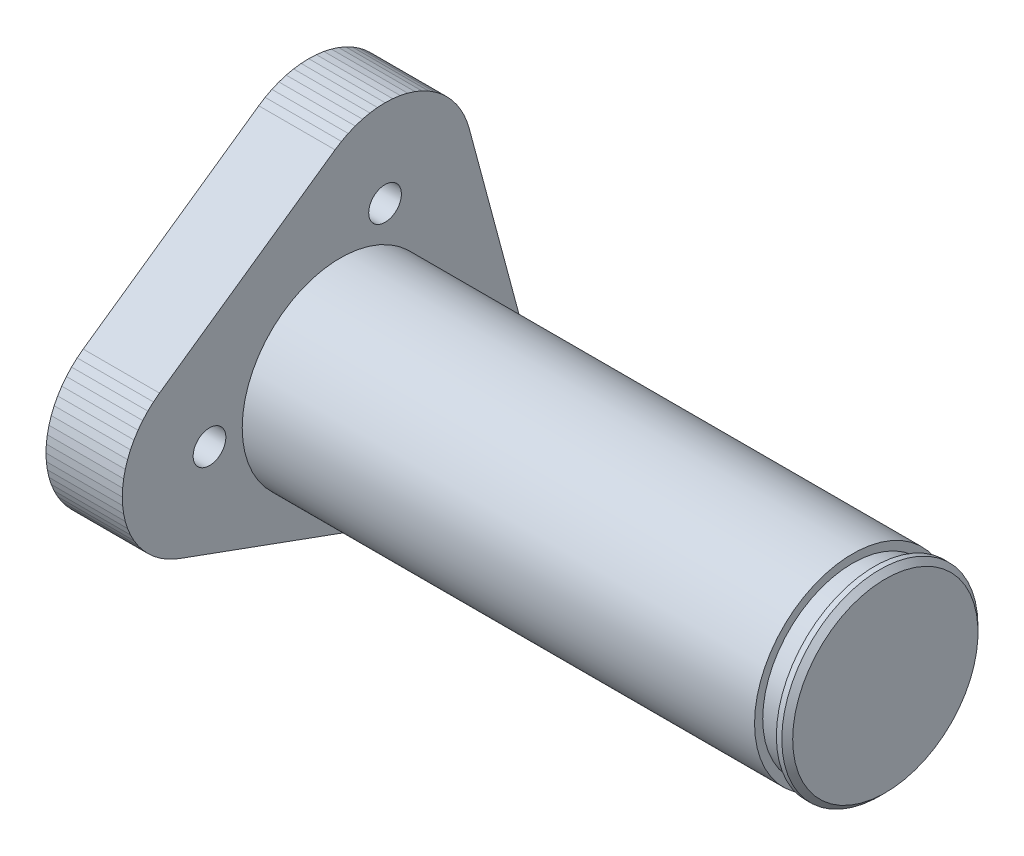
SolidWorks part; units mm, degrees
material "普通碳钢"
ref_plane "前视基准面" through (0, 0, 0) normal (0, 0, 1) x (1, 0, 0)
ref_plane "上视基准面" through (0, 0, 0) normal (0, 1, 0) x (1, 0, 0)
ref_plane "右视基准面" through (0, 0, 0) normal (1, 0, 0) x (0, 0, -1)
other "Configuration Table"
sketch "草图1" plane through (0, 0, 0) normal (0, 0, 1) x (1, 0, 0)
  line L0 (7, 0) -> (7, 9)
  line L1 (7, 9) -> (54, 9)
  line L2 (54, 9) -> (54, 8.25)
  line L3 (54, 8.25) -> (56, 8.25)
  line L4 (56, 8.25) -> (56, 9)
  line L5 (56, 9) -> (56.5, 9)
  line L6 (56.5, 9) -> (57, 8.5)
  line L7 (57, 8.5) -> (57, 0)
  line L8 (57, 0) -> (7, 0)
  line L9 (2, 0) -> (62, 0) construction
revolve "旋转1" add sketch "草图1" angle 360 about L9
sketch "草图2" plane through (0, 0, 0) normal (1, 0, 0) x (0, 0, -1)
  line L0 (-20, 0) -> (-19.9696, -0.6973)
  line L1 (-19.9696, -0.6973) -> (-19.8785, -1.3892)
  line L2 (-19.8785, -1.3892) -> (-19.7274, -2.0705)
  line L3 (-19.7274, -2.0705) -> (-19.5175, -2.7362)
  line L4 (-19.5175, -2.7362) -> (-19.2505, -3.3809)
  line L5 (-19.2505, -3.3809) -> (-18.9282, -4)
  line L6 (-18.9282, -4) -> (-18.5532, -4.5886)
  line L7 (-18.5532, -4.5886) -> (-18.1284, -5.1423)
  line L8 (-18.1284, -5.1423) -> (-17.6568, -5.6569)
  line L9 (-17.6568, -5.6569) -> (-17.1423, -6.1284)
  line L10 (-17.1423, -6.1284) -> (-16.5886, -6.5532)
  line L11 (-16.5886, -6.5532) -> (-16, -6.9282)
  line L12 (-16, -6.9282) -> (-15.381, -7.2505)
  line L13 (-15.381, -7.2505) -> (-14.7362, -7.5175)
  line L14 (-14.7362, -7.5175) -> (6.4564, -15.231)
  line L15 (6.4564, -15.231) -> (7.122, -15.4409)
  line L16 (7.122, -15.4409) -> (7.8034, -15.5919)
  line L17 (7.8034, -15.5919) -> (8.4953, -15.683)
  line L18 (8.4953, -15.683) -> (9.1925, -15.7134)
  line L19 (9.1925, -15.7134) -> (9.8898, -15.683)
  line L20 (9.8898, -15.683) -> (10.5817, -15.5919)
  line L21 (10.5817, -15.5919) -> (11.2631, -15.4409)
  line L22 (11.2631, -15.4409) -> (11.9287, -15.231)
  line L23 (11.9287, -15.231) -> (12.5735, -14.9639)
  line L24 (12.5735, -14.9639) -> (13.1925, -14.6417)
  line L25 (13.1925, -14.6417) -> (13.7811, -14.2667)
  line L26 (13.7811, -14.2667) -> (14.3348, -13.8418)
  line L27 (14.3348, -13.8418) -> (14.8494, -13.3703)
  line L28 (14.8494, -13.3703) -> (15.3209, -12.8558)
  line L29 (15.3209, -12.8558) -> (15.7457, -12.3021)
  line L30 (15.7457, -12.3021) -> (16.1207, -11.7134)
  line L31 (16.1207, -11.7134) -> (16.443, -11.0944)
  line L32 (16.443, -11.0944) -> (16.7101, -10.4496)
  line L33 (16.7101, -10.4496) -> (16.9199, -9.784)
  line L34 (16.9199, -9.784) -> (17.071, -9.1026)
  line L35 (17.071, -9.1026) -> (17.1621, -8.4107)
  line L36 (17.1621, -8.4107) -> (17.1925, -7.7134)
  line L37 (17.1925, -7.7134) -> (17.1621, -7.0162)
  line L38 (17.1621, -7.0162) -> (17.071, -6.3243)
  line L39 (17.071, -6.3243) -> (16.9199, -5.6429)
  line L40 (16.9199, -5.6429) -> (11.8316, 13.3469)
  line L41 (11.8316, 13.3469) -> (11.6218, 14.0125)
  line L42 (11.6218, 14.0125) -> (11.3547, 14.6573)
  line L43 (11.3547, 14.6573) -> (11.0324, 15.2763)
  line L44 (11.0324, 15.2763) -> (10.6575, 15.8649)
  line L45 (10.6575, 15.8649) -> (10.2326, 16.4186)
  line L46 (10.2326, 16.4186) -> (9.7611, 16.9332)
  line L47 (9.7611, 16.9332) -> (9.2465, 17.4047)
  line L48 (9.2465, 17.4047) -> (8.6928, 17.8295)
  line L49 (8.6928, 17.8295) -> (8.1042, 18.2045)
  line L50 (8.1042, 18.2045) -> (7.4852, 18.5268)
  line L51 (7.4852, 18.5268) -> (6.8404, 18.7938)
  line L52 (6.8404, 18.7938) -> (6.1748, 19.0037)
  line L53 (6.1748, 19.0037) -> (5.4934, 19.1548)
  line L54 (5.4934, 19.1548) -> (4.8015, 19.2459)
  line L55 (4.8015, 19.2459) -> (4.1042, 19.2763)
  line L56 (4.1042, 19.2763) -> (3.407, 19.2459)
  line L57 (3.407, 19.2459) -> (2.7151, 19.1548)
  line L58 (2.7151, 19.1548) -> (2.0337, 19.0037)
  line L59 (2.0337, 19.0037) -> (1.3681, 18.7938)
  line L60 (1.3681, 18.7938) -> (0.7233, 18.5268)
  line L61 (0.7233, 18.5268) -> (0.1042, 18.2045)
  line L62 (0.1042, 18.2045) -> (-0.4844, 17.8295)
  line L63 (-0.4844, 17.8295) -> (-16.5886, 6.5532)
  line L64 (-16.5886, 6.5532) -> (-17.1423, 6.1284)
  line L65 (-17.1423, 6.1284) -> (-17.6568, 5.6569)
  line L66 (-17.6568, 5.6569) -> (-18.1284, 5.1423)
  line L67 (-18.1284, 5.1423) -> (-18.5532, 4.5886)
  line L68 (-18.5532, 4.5886) -> (-18.9282, 4)
  line L69 (-18.9282, 4) -> (-19.2505, 3.3809)
  line L70 (-19.2505, 3.3809) -> (-19.5175, 2.7362)
  line L71 (-19.5175, 2.7362) -> (-19.7274, 2.0705)
  line L72 (-19.7274, 2.0705) -> (-19.8785, 1.3892)
  line L73 (-19.8785, 1.3892) -> (-19.9696, 0.6973)
  line L74 (-19.9696, 0.6973) -> (-20, 0)
extrude "02_HEAD" add sketch "草图2" along normal blind 7
sketch "草图3" plane through (0, 0, 0) normal (1, 0, 0) x (0, 0, -1)
  circle A0 centre (-12, 0) radius 1.5
  circle A1 centre (4.1042, 11.2763) radius 1.5
  circle A2 centre (9.1925, -7.7135) radius 1.5
extrude "03_SCREW_HOLES" cut sketch "草图3" along normal through all
sketch "草图4" plane through (0, 0, 0) normal (1, 0, 0) x (0, 0, -1)
  circle A0 centre (-12, 0) radius 2.75
  circle A1 centre (4.1042, 11.2763) radius 2.75
  circle A2 centre (9.1925, -7.7135) radius 2.75
extrude "04_CBORE" cut sketch "草图4" along normal blind 3
sketch "草图5" plane through (0, 0, 0) normal (1, 0, 0) x (0, 0, -1)
  circle A0 centre (0, 0) radius 3.4
extrude "05_M8_TAP" cut sketch "草图5" along normal blind 24
